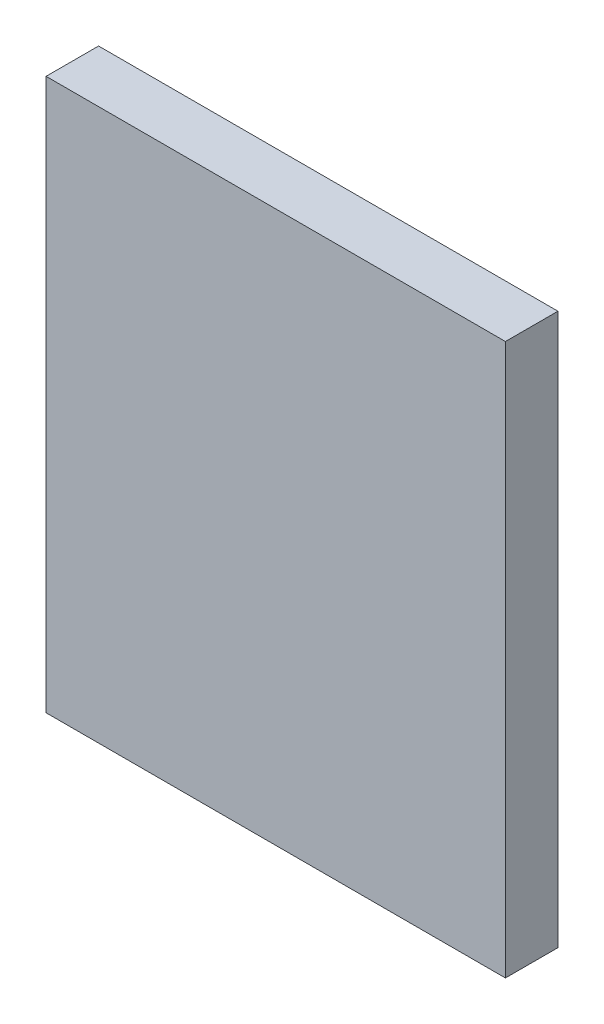
SolidWorks part; units mm, degrees
ref_plane "Alzado" through (0, 0, 0) normal (0, 0, 1) x (1, 0, 0)
ref_plane "Planta" through (0, 0, 0) normal (0, 1, 0) x (1, 0, 0)
ref_plane "Vista lateral" through (0, 0, 0) normal (1, 0, 0) x (0, 0, -1)
sketch "Croquis1" plane through (0, 0, 0) normal (0, 0, 1) x (1, 0, 0)
  line L1 (0, 0) -> (35, 0)
  line L2 (0, 0) -> (0, -42)
  line L3 (0, -42) -> (35, -42)
  line L4 (35, 0) -> (35, -42)
  dimension "D1" = 42
  dimension "D2" = 35
extrude "Saliente-Extruir1" add sketch "Croquis1" along normal blind 4
